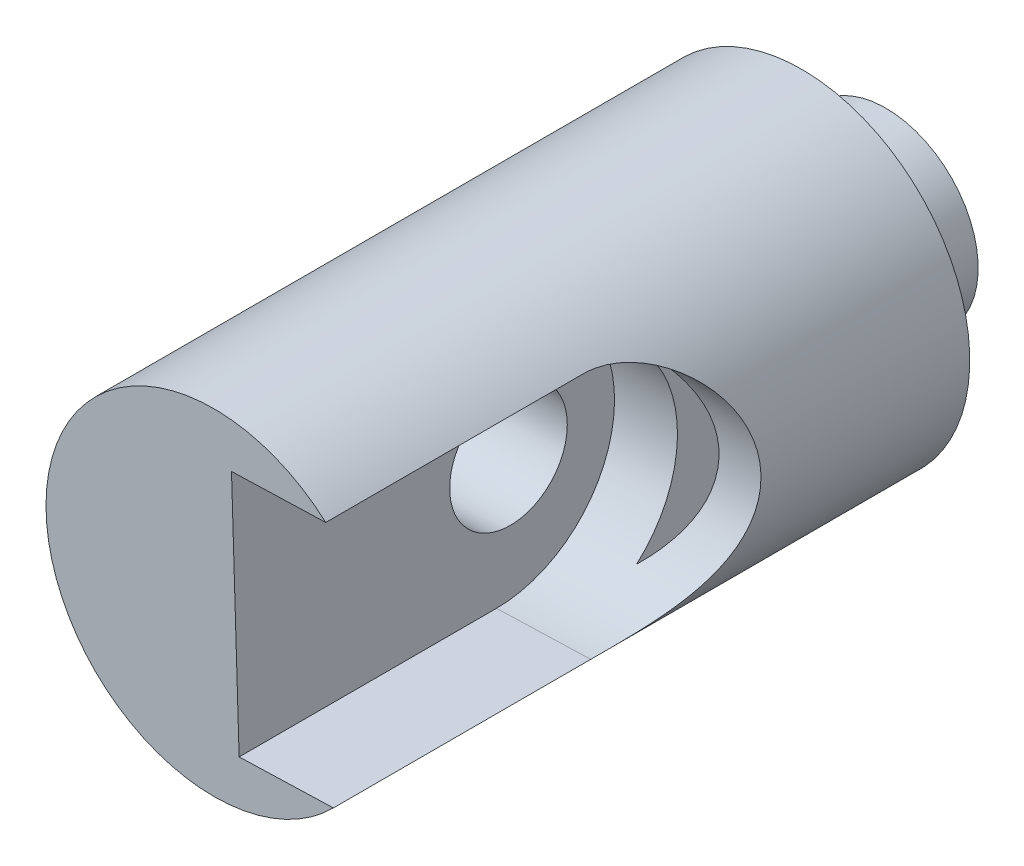
SolidWorks part; units mm, degrees
ref_plane "Front Plane" through (0, 0, 0) normal (0, 0, 1) x (1, 0, 0)
ref_plane "Top Plane" through (0, 0, 0) normal (0, 1, 0) x (1, 0, 0)
ref_plane "Right Plane" through (0, 0, 0) normal (1, 0, 0) x (0, 0, -1)
sketch "Sketch2" plane through (0, 0, 0) normal (0, 0, 1) x (1, 0, 0)
  circle A0 centre (0, 0) radius 20
  dimension "D1" = 40
extrude "Boss-Extrude1" add sketch "Sketch2" along normal blind 30 from offset 10 offset against normal yes
sketch "Sketch3" plane through (0, 0, 20) normal (0, 0, 1) x (1, 0, 0)
  line L2 (6.8182, 18.8019) -> (6.8182, -18.8019)
  line L4 (-6.8182, 18.8019) -> (-6.8182, -18.8019)
  line L5 (6.0408, 19.0659) -> (-6.0408, -19.0659) construction
  line L6 (6.0408, -19.0659) -> (-6.0408, 19.0659) construction
  circle A0 centre (0, 0) radius 20 construction
  arc A1 (-6.8182, -18.8019) -> (6.8182, -18.8019) centre (0, 0) ccw
  arc A2 (6.8182, 18.8019) -> (-6.8182, 18.8019) centre (0, 0) ccw
  point P0 (0, 0)
sketch "Sketch5" plane through (0, 0, -10) normal (0, 0, -1) x (-1, 0, 0)
  circle A0 centre (0, 0) radius 11
  circle A2 centre (0, 0) radius 20
  circle A3 centre (0, 0) radius 20 construction
  dimension "D1" = 22
  dimension "D2" = 0
extrude "Cut-Extrude1" cut sketch "Sketch5" against normal blind 10
sketch "Sketch7" plane through (0, 0, 20) normal (0, 0, 1) x (1, 0, 0)
  circle A0 centre (0, 0) radius 20
extrude "Boss-Extrude2" add sketch "Sketch7" along normal blind 50
sketch "Sketch8" plane through (0, 0, 70) normal (0, 0, 1) x (1, 0, 0)
  line L0 (9.6905, 11.4496) -> (10.3893, -10.8195)
  arc A0 (9.6905, 11.4496) -> (10.3893, -10.8195) centre (0, 0) ccw
  circle A1 centre (0, 0) radius 15
  circle M2 centre (0, 0) radius 20
extrude "Cut-Extrude2" cut sketch "Sketch8" against normal blind 50 contours L0 M2
sketch "Sketch9" plane through (10.0399, 0.3151, 0) normal (0.9995, 0.0314, 0) x (0, 0, -1)
  line L0 (-39.352, 14.5) -> (-72.5991, 14.5)
  line L1 (-72.5991, 14.5) -> (-72.5991, -14.5)
  line L2 (-72.5991, -14.5) -> (-39.352, -14.5)
  arc A0 (-39.352, -14.5) -> (-39.352, 14.5) centre (-39.352, 0) ccw
  dimension "D1" = 29
extrude "Cut-Extrude3" cut sketch "Sketch9" along normal through all from offset 7.5 offset against normal yes
sketch "Sketch10" plane through (2.5436, 0.0798, 0) normal (0.9995, 0.0314, 0) x (0, 0, -1)
  circle A0 centre (-37.4735, 0) radius 7
  dimension "D1" = 14
extrude "Cut-Extrude4" cut sketch "Sketch10" against normal through all
